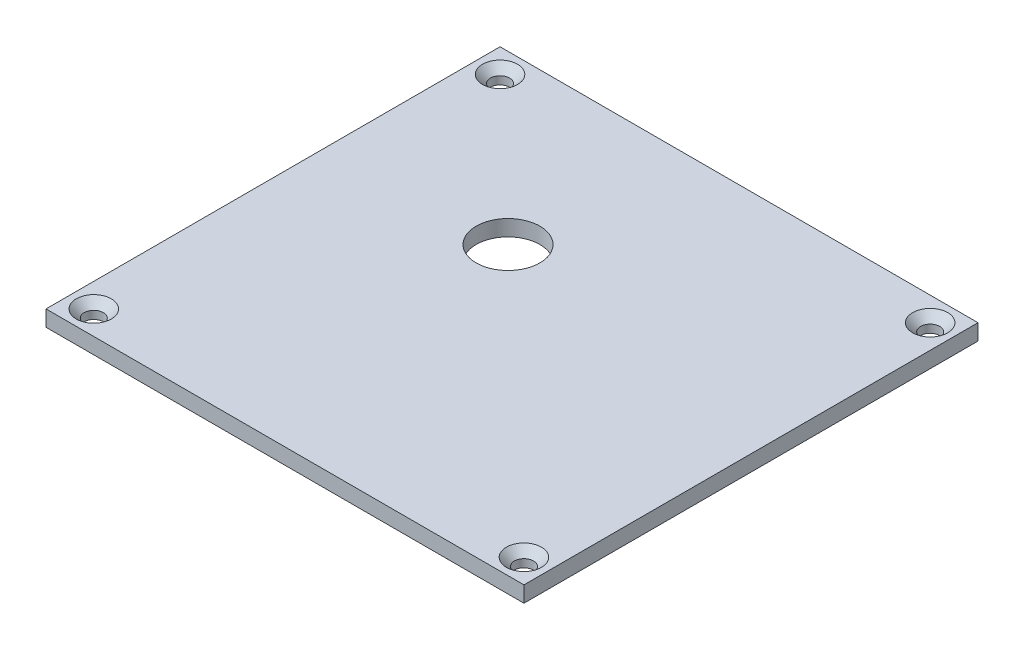
SolidWorks part; units mm, degrees
ref_plane "Front Plane" through (0, 0, 0) normal (0, 0, 1) x (1, 0, 0)
ref_plane "Top Plane" through (0, 0, 0) normal (0, 1, 0) x (1, 0, 0)
ref_plane "Right Plane" through (0, 0, 0) normal (1, 0, 0) x (0, 0, -1)
sketch "Sketch1" plane through (0, 0, 0) normal (0, 1, 0) x (1, 0, 0)
  line L1 (-30, -28.5) -> (30, -28.5)
  line L2 (-30, -28.5) -> (-30, 28.5)
  line L3 (-30, 28.5) -> (30, 28.5)
  line L4 (30, -28.5) -> (30, 28.5)
  line L5 (-30, -28.5) -> (30, 28.5) construction
  line L6 (-30, 28.5) -> (30, -28.5) construction
  point P0 (0, 0)
  dimension "D1" = 60
  dimension "D2" = 57
extrude "Boss-Extrude1" add sketch "Sketch1" along normal blind 2
hole_wizard "CSK for M2 Countersunk Flat Head Screw1" positions "Sketch2" profile "Sketch3" countersink size "M2" standard "ISO" end condition through all
sketch "Sketch2" plane through (0, 2, 0) normal (0, 1, 0) x (1, 0, 0)
  line L0 (-30, -28.5) -> (30, -28.5) construction
  line L1 (-30, 28.5) -> (-30, -28.5) construction
  line L2 (30, -28.5) -> (30, 28.5) construction
  line L3 (30, 28.5) -> (-30, 28.5) construction
  point P0 (-27, 25.5)
  point P2 (27, 25.5)
  point P4 (27, -25.5)
  point P6 (-27, -25.5)
  dimension "D1" = 3
  dimension "D2" = 3
  dimension "D3" = 3
  dimension "D4" = 3
sketch "Sketch3" plane through (-27, 2, -25.5) normal (1, 0, 0) x (0, 0, 1)
  line L0 (0, 0) -> (0, 2)
  line L1 (0, 2) -> (1.2, 2)
  line L2 (1.2, 2) -> (1.2, 1)
  line L3 (1.2, 1) -> (2.2, 0)
  line L5 (2.2, 0) -> (0, 0)
  line L6 (-1.2, 1) -> (-2.2, 0) construction
  line L11 (0, -6.35) -> (0, 107.95) construction
  dimension "Thru Hole Dia." = 2.4
  dimension "Thru Hole Depth" = 2
  dimension "Near C'Sink Dia." = 4.4
  dimension "Near C'Sink Angle" = 90
sketch "Sketch4" plane through (0, 2, 0) normal (0, 1, 0) x (1, 0, 0)
  circle A0 centre (-8, 7.5) radius 4
  circle A6 centre (-27, 25.5) radius 2.2 construction
  circle A7 centre (-27, 25.5) radius 1.2 construction
  dimension "D2" = 8
  dimension "D3" = 18
  dimension "D1" = 19
extrude "Cut-Extrude1" cut sketch "Sketch4" against normal blind 2
